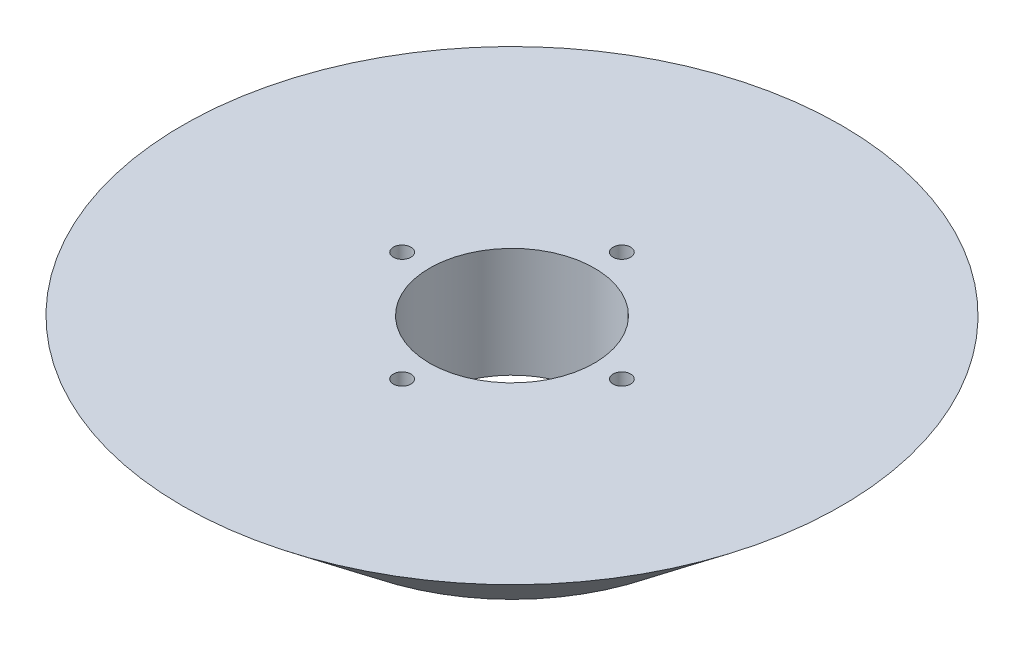
SolidWorks part; units mm, degrees
ref_plane "正面" through (0, 0, 0) normal (0, 0, 1) x (1, 0, 0)
ref_plane "平面" through (0, 0, 0) normal (0, 1, 0) x (1, 0, 0)
ref_plane "右側面" through (0, 0, 0) normal (1, 0, 0) x (0, 0, -1)
sketch "ｽｹｯﾁ1" plane through (0, 0, 0) normal (0, 1, 0) x (1, 0, 0)
  circle A0 centre (0, 0) radius 35
  dimension "D1" = 70
ref_plane "平面1" through (0, 20, 0) normal (0, 1, 0) x (1, 0, 0)
sketch "ｽｹｯﾁ2" plane through (0, 20, 0) normal (0, 1, 0) x (1, 0, 0)
  circle A0 centre (0, 0) radius 60
  dimension "D1" = 120
loft "ﾛﾌﾄ1" add profiles "ｽｹｯﾁ2", "ｽｹｯﾁ1"
sketch "ｽｹｯﾁ3" plane through (0, 20, 0) normal (0, 1, 0) x (1, 0, 0)
  line L0 (0, 20) -> (0, 0) construction
  line L1 (-20, 0) -> (0, 0) construction
  line L2 (0, 0) -> (0, -20) construction
  circle A0 centre (0, 20) radius 1.6
  circle A1 centre (20, 0) radius 1.6
  circle A2 centre (0, -20) radius 1.6
  circle A3 centre (-20, 0) radius 1.6
  circle A4 centre (0, 0) radius 15
  dimension "D1" = 3.2
  dimension "D4" = 30
  dimension "D2" = 20
  dimension "D3" = 4
extrude "ｶｯﾄ - 押し出し1" cut sketch "ｽｹｯﾁ3" against normal through all
